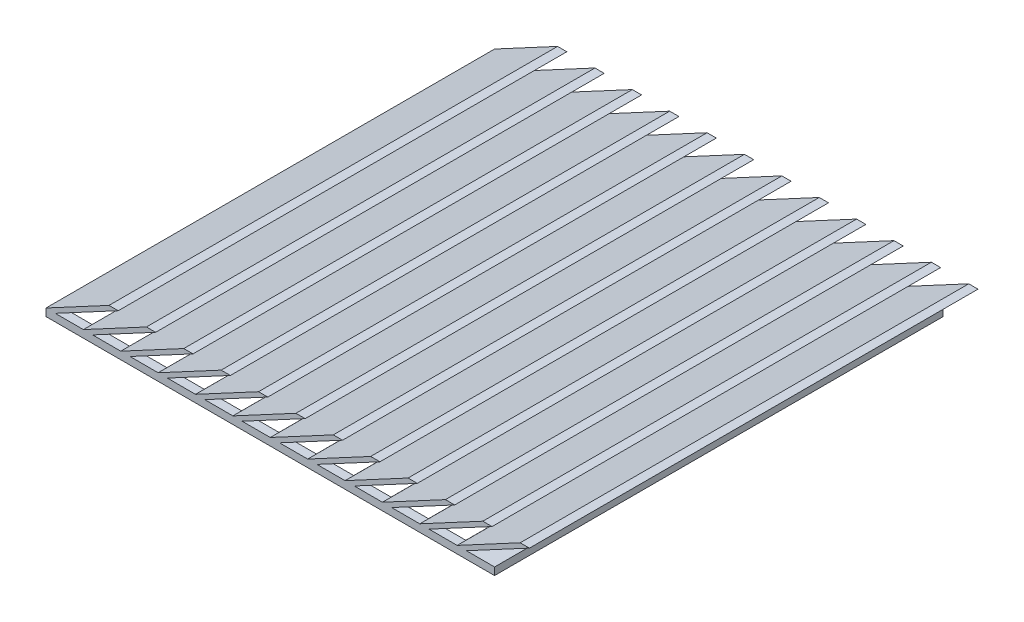
SolidWorks part; units mm, degrees
ref_plane "前视基准面" through (0, 0, 0) normal (0, 0, 1) x (1, 0, 0)
ref_plane "上视基准面" through (0, 0, 0) normal (0, 1, 0) x (1, 0, 0)
ref_plane "右视基准面" through (0, 0, 0) normal (1, 0, 0) x (0, 0, -1)
other "Configuration Table"
sketch "草图2" plane through (0, 0, 0) normal (0, 0, 1) x (1, 0, 0)
  line L0 (0, 2) -> (16.8562, 11.0325)
  line L5 (0, 0) -> (120, 0)
  line L6 (0, 0) -> (0, 2)
  line L7 (2.4765, 2) -> (10, 2)
  line L8 (120, 0) -> (120, 2)
  line L9 (16.8562, 11.0325) -> (19.3327, 11.0325)
  line L10 (19.3327, 11.0325) -> (2.4765, 2)
  line L11 (10, 2) -> (26.8562, 11.0325)
  line L12 (29.3327, 11.0325) -> (12.4765, 2)
  line L13 (26.8562, 11.0325) -> (29.3327, 11.0325)
  line L14 (20, 2) -> (36.8562, 11.0325)
  line L15 (39.3327, 11.0325) -> (22.4765, 2)
  line L16 (36.8562, 11.0325) -> (39.3327, 11.0325)
  line L17 (30, 2) -> (46.8562, 11.0325)
  line L18 (49.3327, 11.0325) -> (32.4765, 2)
  line L19 (46.8562, 11.0325) -> (49.3327, 11.0325)
  line L20 (40, 2) -> (56.8562, 11.0325)
  line L21 (59.3327, 11.0325) -> (42.4765, 2)
  line L22 (56.8562, 11.0325) -> (59.3327, 11.0325)
  line L23 (50, 2) -> (66.8562, 11.0325)
  line L24 (69.3327, 11.0325) -> (52.4765, 2)
  line L25 (66.8562, 11.0325) -> (69.3327, 11.0325)
  line L26 (60, 2) -> (76.8562, 11.0325)
  line L27 (79.3327, 11.0325) -> (62.4765, 2)
  line L28 (76.8562, 11.0325) -> (79.3327, 11.0325)
  line L29 (70, 2) -> (86.8562, 11.0325)
  line L30 (89.3327, 11.0325) -> (72.4765, 2)
  line L31 (86.8562, 11.0325) -> (89.3327, 11.0325)
  line L32 (80, 2) -> (96.8562, 11.0325)
  line L33 (99.3327, 11.0325) -> (82.4765, 2)
  line L34 (96.8562, 11.0325) -> (99.3327, 11.0325)
  line L35 (90, 2) -> (106.8562, 11.0325)
  line L36 (109.3327, 11.0325) -> (92.4765, 2)
  line L37 (106.8562, 11.0325) -> (109.3327, 11.0325)
  line L38 (100, 2) -> (116.8562, 11.0325)
  line L39 (119.3327, 11.0325) -> (102.4765, 2)
  line L40 (116.8562, 11.0325) -> (119.3327, 11.0325)
  line L41 (110, 2) -> (126.8562, 11.0325)
  line L42 (129.3327, 11.0325) -> (112.4765, 2)
  line L43 (126.8562, 11.0325) -> (129.3327, 11.0325)
  line L44 (12.4765, 2) -> (20, 2)
  line L45 (22.4765, 2) -> (30, 2)
  line L46 (32.4765, 2) -> (40, 2)
  line L47 (42.4765, 2) -> (50, 2)
  line L48 (52.4765, 2) -> (60, 2)
  line L49 (62.4765, 2) -> (70, 2)
  line L50 (72.4765, 2) -> (80, 2)
  line L51 (82.4765, 2) -> (90, 2)
  line L52 (92.4765, 2) -> (100, 2)
  line L53 (102.4765, 2) -> (110, 2)
  line L54 (112.4765, 2) -> (120, 2)
  dimension "D1" = 120
  dimension "D2" = 2
  dimension "D3" = 12
extrude "凸台-拉伸1" add sketch "草图2" along normal blind 120
sketch "草图5" plane through (0, 0, 0) normal (0, -1, 0) x (1, 0, 0)
  line L0 (0, 120) -> (120, 120) construction
  line L1 (0, 120) -> (2.48, 120)
  line L2 (2.4764, 117.6535) -> (2.48, 2.48)
  line L3 (9.9999, 117.6535) -> (10, 2.48)
  line L26 (0, 120) -> (0, 0) construction
  line L27 (2.4764, 117.6535) -> (9.9999, 117.6535)
  line L28 (2.48, 2.48) -> (10, 2.48)
  line L29 (110.0001, 2.48) -> (117.5201, 2.48)
  line L30 (120, 120) -> (120, 0) construction
  line L31 (12.4729, 117.6535) -> (19.9964, 117.6535)
  line L32 (0, 0) -> (120, 0) construction
  line L44 (100.2255, 2.48) -> (107.7455, 2.48)
  line L45 (90.451, 2.48) -> (97.971, 2.48)
  line L46 (80.6764, 2.48) -> (88.1964, 2.48)
  line L47 (70.9019, 2.48) -> (78.4219, 2.48)
  line L48 (61.1273, 2.48) -> (68.6473, 2.48)
  line L49 (51.3528, 2.48) -> (58.8728, 2.48)
  line L50 (41.5782, 2.48) -> (49.0982, 2.48)
  line L51 (31.8037, 2.48) -> (39.3237, 2.48)
  line L52 (22.0291, 2.48) -> (29.5491, 2.48)
  line L53 (12.2546, 2.48) -> (19.7746, 2.48)
  line L54 (12.4729, 117.6535) -> (12.4765, 2.48)
  line L55 (19.9964, 117.6535) -> (19.9965, 2.48)
  line L56 (12.4765, 2.48) -> (19.9965, 2.48)
  line L57 (22.4694, 117.6535) -> (29.9929, 117.6535)
  line L58 (22.4694, 117.6535) -> (22.4729, 2.48)
  line L59 (29.9929, 117.6535) -> (29.9929, 2.48)
  line L60 (22.4729, 2.48) -> (29.9929, 2.48)
  line L61 (32.4658, 117.6535) -> (39.9894, 117.6535)
  line L62 (32.4658, 117.6535) -> (32.4694, 2.48)
  line L63 (39.9894, 117.6535) -> (39.9894, 2.48)
  line L64 (32.4694, 2.48) -> (39.9894, 2.48)
  line L65 (42.4623, 117.6535) -> (49.9858, 117.6535)
  line L66 (42.4623, 117.6535) -> (42.4659, 2.48)
  line L67 (49.9858, 117.6535) -> (49.9859, 2.48)
  line L68 (42.4659, 2.48) -> (49.9859, 2.48)
  line L69 (52.4588, 117.6535) -> (59.9823, 117.6535)
  line L70 (52.4588, 117.6535) -> (52.4624, 2.48)
  line L71 (59.9823, 117.6535) -> (59.9824, 2.48)
  line L72 (52.4624, 2.48) -> (59.9824, 2.48)
  line L73 (62.4552, 117.6535) -> (69.9788, 117.6535)
  line L74 (62.4552, 117.6535) -> (62.4588, 2.48)
  line L75 (69.9788, 117.6535) -> (69.9788, 2.48)
  line L76 (62.4588, 2.48) -> (69.9788, 2.48)
  line L77 (72.4517, 117.6535) -> (79.9752, 117.6535)
  line L78 (72.4517, 117.6535) -> (72.4553, 2.48)
  line L79 (79.9752, 117.6535) -> (79.9753, 2.48)
  line L80 (72.4553, 2.48) -> (79.9753, 2.48)
  line L81 (82.4482, 117.6535) -> (89.9717, 117.6535)
  line L82 (82.4482, 117.6535) -> (82.4518, 2.48)
  line L83 (89.9717, 117.6535) -> (89.9718, 2.48)
  line L84 (82.4518, 2.48) -> (89.9718, 2.48)
  line L85 (92.4447, 117.6535) -> (99.9682, 117.6535)
  line L86 (92.4447, 117.6535) -> (92.4483, 2.48)
  line L87 (99.9682, 117.6535) -> (99.9683, 2.48)
  line L88 (92.4483, 2.48) -> (99.9683, 2.48)
  line L89 (102.4411, 117.6535) -> (109.9647, 117.6535)
  line L90 (102.4411, 117.6535) -> (102.4447, 2.48)
  line L91 (109.9647, 117.6535) -> (109.9647, 2.48)
  line L92 (102.4447, 2.48) -> (109.9647, 2.48)
  point P0 (2.48, 120)
  point P6 (10, 120)
  point P11 (0, 117.52)
  point P12 (0, 2.48)
  point P74 (117.5201, 0)
  dimension "D1" = 2.48
  dimension "D2" = 7.52
  dimension "D4" = 2.48
  dimension "D5" = 2.48
  dimension "D6" = 2.48
  dimension "D8" = 2.48
  dimension "D9" = 7.5235
  dimension "D10" = 7.52
  dimension "D11" = 2.48
  dimension "D12" = 2.4799
  dimension "D13" = 2.48
  dimension "D3" = 11
extrude "切除-拉伸1" cut sketch "草图5" against normal blind 2 contours L2 L28 L3 L27 | L53 L56 L55 L31 L54 | L51 L64 L63 L61 L62 | L50 L68 L67 L65 L66 | L49 L72 L71 L69 L70 | L48 L76 L75 L73 L74 | L47 L80 L79 L77 L78 | L46 L84 L83 L81 L82 | L45 L88 L87 L85 L86 | L44 L92 L91 L89 L90 | L58 L60 L59 L57
